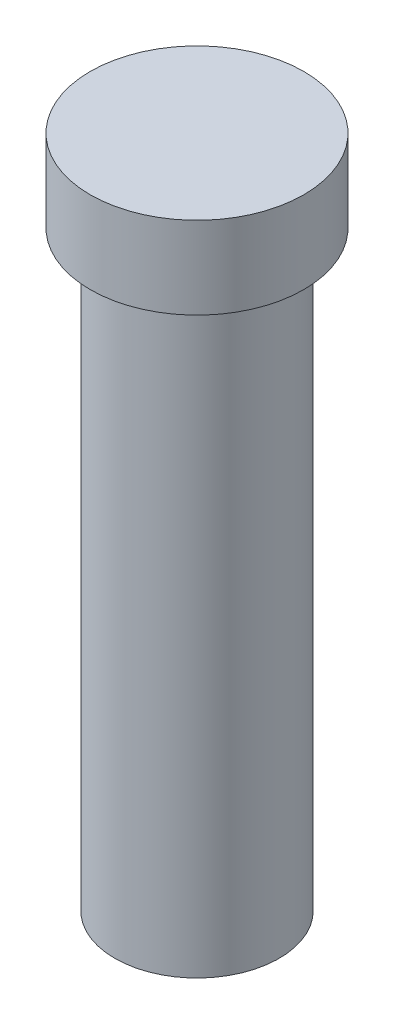
SolidWorks part; units mm, degrees
material "1.2316 (X36CrMo17)"
ref_plane "Front Plane" through (0, 0, 0) normal (0, 0, 1) x (1, 0, 0)
ref_plane "Top Plane" through (0, 0, 0) normal (0, 1, 0) x (1, 0, 0)
ref_plane "Right Plane" through (0, 0, 0) normal (1, 0, 0) x (0, 0, -1)
sketch "Sketch1" plane through (0, 0, 0) normal (0, 0, 1) x (1, 0, 0)
  line L0 (0, 0) -> (6.5, 0)
  line L1 (6.5, 0) -> (6.5, -5)
  line L2 (6.5, -5) -> (5, -5)
  line L3 (5, -5) -> (5, -41)
  line L4 (5, -41) -> (0, -41)
  line L5 (0, -41) -> (0, 0)
  line L6 (0, 8.477) -> (0, -63.2688) construction
  dimension "D1" = 13
  dimension "D2" = 10
  dimension "D3" = 5
  dimension "D4" = 41
revolve "Revolve1" add sketch "Sketch1" angle 360 about L6
